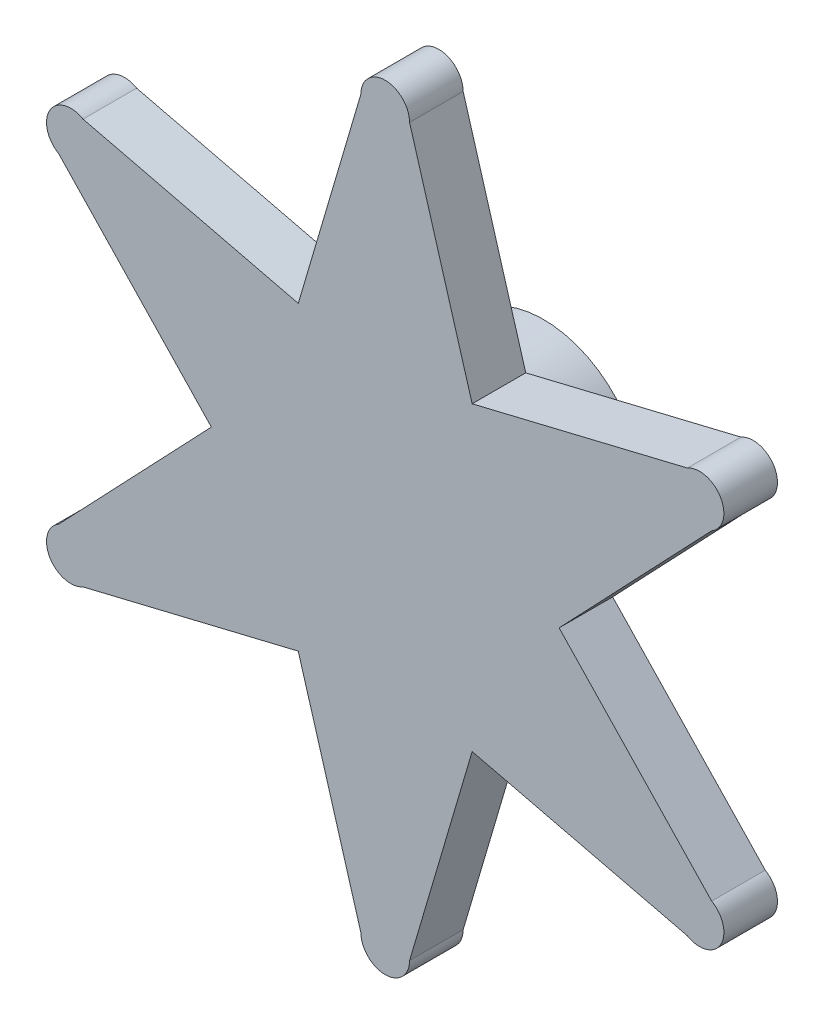
SolidWorks part; units mm, degrees
ref_plane "Front Plane" through (0, 0, 0) normal (0, 0, 1) x (1, 0, 0)
ref_plane "Top Plane" through (0, 0, 0) normal (0, 1, 0) x (1, 0, 0)
ref_plane "Right Plane" through (0, 0, 0) normal (1, 0, 0) x (0, 0, -1)
sketch "Sketch1" plane through (0, 0, 0) normal (0, 0, 1) x (1, 0, 0)
  line L200 (11.1072, 2.7986) -> (11.0109, 2.9361)
  line L201 (11.0109, 2.9361) -> (10.9327, 2.7877)
  line L202 (10.9327, 2.7877) -> (10.828, 2.9188)
  line L203 (10.828, 2.9188) -> (10.7592, 2.7657)
  line L204 (10.7592, 2.7657) -> (10.6465, 2.89)
  line L205 (10.6465, 2.89) -> (10.5874, 2.733)
  line L206 (10.5874, 2.733) -> (10.4672, 2.8499)
  line L207 (10.4672, 2.8499) -> (10.4181, 2.6895)
  line L208 (10.4181, 2.6895) -> (10.2907, 2.7987)
  line L209 (10.2907, 2.7987) -> (10.2518, 2.6355)
  line L210 (10.2518, 2.6355) -> (10.1178, 2.7364)
  line L211 (10.1178, 2.7364) -> (10.0893, 2.5711)
  line L212 (10.0893, 2.5711) -> (9.9492, 2.6635)
  line L213 (9.9492, 2.6635) -> (9.9311, 2.4967)
  line L214 (9.9311, 2.4967) -> (9.7855, 2.58)
  line L215 (9.7855, 2.58) -> (9.7778, 2.4124)
  line L216 (9.7778, 2.4124) -> (9.6273, 2.4865)
  line L217 (9.6273, 2.4865) -> (9.6302, 2.3187)
  line L218 (9.6302, 2.3187) -> (9.4753, 2.3832)
  line L219 (9.4753, 2.3832) -> (9.4888, 2.216)
  line L220 (9.4888, 2.216) -> (9.3301, 2.2706)
  line L221 (9.3301, 2.2706) -> (9.354, 2.1045)
  line L222 (9.354, 2.1045) -> (9.1923, 2.1491)
  line L223 (9.1923, 2.1491) -> (9.2266, 1.9848)
  line L224 (9.2266, 1.9848) -> (9.0624, 2.0191)
  line L225 (9.0624, 2.0191) -> (9.1069, 1.8574)
  line L226 (9.1069, 1.8574) -> (8.9408, 1.8813)
  line L227 (8.9408, 1.8813) -> (8.9955, 1.7227)
  line L228 (8.9955, 1.7227) -> (8.8282, 1.7361)
  line L229 (8.8282, 1.7361) -> (8.8927, 1.5812)
  line L230 (8.8927, 1.5812) -> (8.7249, 1.5841)
  line L231 (8.7249, 1.5841) -> (8.799, 1.4336)
  line L232 (8.799, 1.4336) -> (8.6314, 1.426)
  line L233 (8.6314, 1.426) -> (8.7148, 1.2804)
  line L234 (8.7148, 1.2804) -> (8.548, 1.2623)
  line L235 (8.548, 1.2623) -> (8.6403, 1.1222)
  line L236 (8.6403, 1.1222) -> (8.475, 1.0936)
  line L237 (8.475, 1.0936) -> (8.576, 0.9596)
  line L238 (8.576, 0.9596) -> (8.4128, 0.9207)
  line L239 (8.4128, 0.9207) -> (8.5219, 0.7933)
  line L240 (8.5219, 0.7933) -> (8.3615, 0.7443)
  line L241 (8.3615, 0.7443) -> (8.4785, 0.624)
  line L242 (8.4785, 0.624) -> (8.3214, 0.565)
  line L243 (8.3214, 0.565) -> (8.4457, 0.4522)
  line L244 (8.4457, 0.4522) -> (8.2927, 0.3835)
  line L245 (8.2927, 0.3835) -> (8.4238, 0.2788)
  line L246 (8.4238, 0.2788) -> (8.2754, 0.2005)
  line L247 (8.2754, 0.2005) -> (8.4128, 0.1043)
  line L248 (8.4128, 0.1043) -> (8.2696, 0.0169)
  line L249 (8.2696, 0.0169) -> (8.4128, -0.0706)
  line L250 (8.4128, -0.0706) -> (8.2754, -0.1668)
  line L251 (8.2754, -0.1668) -> (8.4238, -0.245)
  line L252 (8.4238, -0.245) -> (8.2927, -0.3497)
  line L253 (8.2927, -0.3497) -> (8.4457, -0.4185)
  line L254 (8.4457, -0.4185) -> (8.3214, -0.5312)
  line L255 (8.3214, -0.5312) -> (8.4785, -0.5903)
  line L256 (8.4785, -0.5903) -> (8.3615, -0.7105)
  line L257 (8.3615, -0.7105) -> (8.5219, -0.7596)
  line L258 (8.5219, -0.7596) -> (8.4128, -0.887)
  line L259 (8.4128, -0.887) -> (8.576, -0.9259)
  line L260 (8.576, -0.9259) -> (8.475, -1.0599)
  line L261 (8.475, -1.0599) -> (8.6403, -1.0884)
  line L262 (8.6403, -1.0884) -> (8.548, -1.2285)
  line L263 (8.548, -1.2285) -> (8.7148, -1.2466)
  line L264 (8.7148, -1.2466) -> (8.6314, -1.3922)
  line L265 (8.6314, -1.3922) -> (8.799, -1.3999)
  line L266 (8.799, -1.3999) -> (8.7249, -1.5504)
  line L267 (8.7249, -1.5504) -> (8.8927, -1.5475)
  line L268 (8.8927, -1.5475) -> (8.8282, -1.7024)
  line L269 (8.8282, -1.7024) -> (8.9955, -1.6889)
  line L270 (8.9955, -1.6889) -> (8.9408, -1.8476)
  line L271 (8.9408, -1.8476) -> (9.1069, -1.8237)
  line L272 (9.1069, -1.8237) -> (9.0624, -1.9854)
  line L273 (9.0624, -1.9854) -> (9.2266, -1.9511)
  line L274 (9.2266, -1.9511) -> (9.1923, -2.1153)
  line L275 (9.1923, -2.1153) -> (9.354, -2.0708)
  line L276 (9.354, -2.0708) -> (9.3301, -2.2369)
  line L277 (9.3301, -2.2369) -> (9.4888, -2.1822)
  line L278 (9.4888, -2.1822) -> (9.4753, -2.3495)
  line L279 (9.4753, -2.3495) -> (9.6302, -2.285)
  line L280 (9.6302, -2.285) -> (9.6273, -2.4528)
  line L281 (9.6273, -2.4528) -> (9.7778, -2.3787)
  line L282 (9.7778, -2.3787) -> (9.7855, -2.5463)
  line L283 (9.7855, -2.5463) -> (9.9311, -2.4629)
  line L284 (9.9311, -2.4629) -> (9.9492, -2.6297)
  line L285 (9.9492, -2.6297) -> (10.0893, -2.5374)
  line L286 (10.0893, -2.5374) -> (10.1178, -2.7027)
  line L287 (10.1178, -2.7027) -> (10.2518, -2.6017)
  line L288 (10.2518, -2.6017) -> (10.2907, -2.7649)
  line L289 (10.2907, -2.7649) -> (10.4181, -2.6558)
  line L290 (10.4181, -2.6558) -> (10.4672, -2.8162)
  line L291 (10.4672, -2.8162) -> (10.5874, -2.6992)
  line L292 (10.5874, -2.6992) -> (10.6465, -2.8563)
  line L293 (10.6465, -2.8563) -> (10.7592, -2.732)
  line L294 (10.7592, -2.732) -> (10.828, -2.885)
  line L295 (10.828, -2.885) -> (10.9327, -2.7539)
  line L296 (10.9327, -2.7539) -> (11.0109, -2.9023)
  line L297 (11.0109, -2.9023) -> (11.1072, -2.7649)
  line L298 (11.1072, -2.7649) -> (11.1946, -2.9081)
  line L299 (11.1946, -2.9081) -> (11.282, -2.7649)
  line L300 (11.282, -2.7649) -> (11.3782, -2.9023)
  line L301 (11.3782, -2.9023) -> (11.4565, -2.7539)
  line L302 (11.4565, -2.7539) -> (11.5612, -2.885)
  line L303 (11.5612, -2.885) -> (11.6299, -2.732)
  line L304 (11.6299, -2.732) -> (11.7427, -2.8563)
  line L305 (11.7427, -2.8563) -> (11.8017, -2.6992)
  line L306 (11.8017, -2.6992) -> (11.922, -2.8162)
  line L307 (11.922, -2.8162) -> (11.971, -2.6558)
  line L308 (11.971, -2.6558) -> (12.0984, -2.7649)
  line L309 (12.0984, -2.7649) -> (12.1373, -2.6017)
  line L310 (12.1373, -2.6017) -> (12.2713, -2.7027)
  line L311 (12.2713, -2.7027) -> (12.2999, -2.5374)
  line L312 (12.2999, -2.5374) -> (12.44, -2.6297)
  line L313 (12.44, -2.6297) -> (12.4581, -2.4629)
  line L314 (12.4581, -2.4629) -> (12.6037, -2.5463)
  line L315 (12.6037, -2.5463) -> (12.6113, -2.3787)
  line L316 (12.6113, -2.3787) -> (12.7618, -2.4528)
  line L317 (12.7618, -2.4528) -> (12.7589, -2.285)
  line L318 (12.7589, -2.285) -> (12.9138, -2.3495)
  line L319 (12.9138, -2.3495) -> (12.9004, -2.1822)
  line L320 (12.9004, -2.1822) -> (13.059, -2.2369)
  line L321 (13.059, -2.2369) -> (13.0351, -2.0708)
  line L322 (13.0351, -2.0708) -> (13.1968, -2.1153)
  line L323 (13.1968, -2.1153) -> (13.1625, -1.9511)
  line L324 (13.1625, -1.9511) -> (13.3268, -1.9854)
  line L325 (13.3268, -1.9854) -> (13.2822, -1.8237)
  line L326 (13.2822, -1.8237) -> (13.4483, -1.8476)
  line L327 (13.4483, -1.8476) -> (13.3937, -1.6889)
  line L328 (13.3937, -1.6889) -> (13.5609, -1.7024)
  line L329 (13.5609, -1.7024) -> (13.4965, -1.5475)
  line L330 (13.4965, -1.5475) -> (13.6642, -1.5504)
  line L331 (13.6642, -1.5504) -> (13.5901, -1.3999)
  line L332 (13.5901, -1.3999) -> (13.7577, -1.3922)
  line L333 (13.7577, -1.3922) -> (13.6744, -1.2466)
  line L334 (13.6744, -1.2466) -> (13.8412, -1.2285)
  line L335 (13.8412, -1.2285) -> (13.7488, -1.0884)
  line L336 (13.7488, -1.0884) -> (13.9141, -1.0599)
  line L337 (13.9141, -1.0599) -> (13.8132, -0.9259)
  line L338 (13.8132, -0.9259) -> (13.9764, -0.887)
  line L339 (13.9764, -0.887) -> (13.8672, -0.7596)
  line L340 (13.8672, -0.7596) -> (14.0276, -0.7105)
  line L341 (14.0276, -0.7105) -> (13.9107, -0.5903)
  line L342 (13.9107, -0.5903) -> (14.0677, -0.5312)
  line L343 (14.0677, -0.5312) -> (13.9434, -0.4185)
  line L344 (13.9434, -0.4185) -> (14.0965, -0.3497)
  line L345 (14.0965, -0.3497) -> (13.9654, -0.245)
  line L346 (13.9654, -0.245) -> (14.1138, -0.1668)
  line L347 (14.1138, -0.1668) -> (13.9763, -0.0706)
  line L348 (13.9763, -0.0706) -> (14.1195, 0.0169)
  line L349 (14.1195, 0.0169) -> (13.9763, 0.1043)
  line L350 (13.9763, 0.1043) -> (14.1138, 0.2005)
  line L351 (14.1138, 0.2005) -> (13.9654, 0.2788)
  line L352 (13.9654, 0.2788) -> (14.0965, 0.3835)
  line L353 (14.0965, 0.3835) -> (13.9434, 0.4522)
  line L354 (13.9434, 0.4522) -> (14.0677, 0.565)
  line L355 (14.0677, 0.565) -> (13.9107, 0.624)
  line L356 (13.9107, 0.624) -> (14.0276, 0.7443)
  line L357 (14.0276, 0.7443) -> (13.8672, 0.7933)
  line L358 (13.8672, 0.7933) -> (13.9764, 0.9207)
  line L359 (13.9764, 0.9207) -> (13.8132, 0.9596)
  line L360 (13.8132, 0.9596) -> (13.9141, 1.0936)
  line L361 (13.9141, 1.0936) -> (13.7488, 1.1222)
  line L362 (13.7488, 1.1222) -> (13.8412, 1.2623)
  line L363 (13.8412, 1.2623) -> (13.6744, 1.2804)
  line L364 (13.6744, 1.2804) -> (13.7577, 1.426)
  line L365 (13.7577, 1.426) -> (13.5901, 1.4336)
  line L366 (13.5901, 1.4336) -> (13.6642, 1.5841)
  line L367 (13.6642, 1.5841) -> (13.4965, 1.5812)
  line L368 (13.4965, 1.5812) -> (13.5609, 1.7361)
  line L369 (13.5609, 1.7361) -> (13.3937, 1.7227)
  line L370 (13.3937, 1.7227) -> (13.4483, 1.8813)
  line L371 (13.4483, 1.8813) -> (13.2822, 1.8574)
  line L372 (13.2822, 1.8574) -> (13.3268, 2.0191)
  line L373 (13.3268, 2.0191) -> (13.1625, 1.9848)
  line L374 (13.1625, 1.9848) -> (13.1968, 2.1491)
  line L375 (13.1968, 2.1491) -> (13.0351, 2.1045)
  line L376 (13.0351, 2.1045) -> (13.059, 2.2706)
  line L377 (13.059, 2.2706) -> (12.9004, 2.216)
  line L378 (12.9004, 2.216) -> (12.9138, 2.3832)
  line L379 (12.9138, 2.3832) -> (12.7589, 2.3187)
  line L380 (12.7589, 2.3187) -> (12.7618, 2.4865)
  line L381 (12.7618, 2.4865) -> (12.6113, 2.4124)
  line L382 (12.6113, 2.4124) -> (12.6037, 2.58)
  line L383 (12.6037, 2.58) -> (12.4581, 2.4967)
  line L384 (12.4581, 2.4967) -> (12.44, 2.6635)
  line L385 (12.44, 2.6635) -> (12.2999, 2.5711)
  line L386 (12.2999, 2.5711) -> (12.2713, 2.7364)
  line L387 (12.2713, 2.7364) -> (12.1373, 2.6355)
  line L388 (12.1373, 2.6355) -> (12.0984, 2.7987)
  line L389 (12.0984, 2.7987) -> (11.971, 2.6895)
  line L390 (11.971, 2.6895) -> (11.922, 2.8499)
  line L391 (11.922, 2.8499) -> (11.8017, 2.733)
  line L392 (11.8017, 2.733) -> (11.7427, 2.89)
  line L393 (11.7427, 2.89) -> (11.6299, 2.7657)
  line L394 (11.6299, 2.7657) -> (11.5612, 2.9188)
  line L395 (11.5612, 2.9188) -> (11.4565, 2.7877)
  line L396 (11.4565, 2.7877) -> (11.3782, 2.9361)
  line L397 (11.3782, 2.9361) -> (11.282, 2.7986)
  line L398 (11.282, 2.7986) -> (11.1946, 2.9418)
  line L399 (11.1946, 2.9418) -> (11.1072, 2.7986)
  line L400 (11.1072, 2.7986) -> (11.0109, 2.9361)
  line L401 (11.0109, 2.9361) -> (10.9327, 2.7877)
  line L402 (10.9327, 2.7877) -> (10.828, 2.9188)
  line L403 (10.828, 2.9188) -> (10.7592, 2.7657)
  line L404 (10.7592, 2.7657) -> (10.6465, 2.89)
  line L405 (10.6465, 2.89) -> (10.5874, 2.733)
  line L406 (10.5874, 2.733) -> (10.4672, 2.8499)
  line L407 (10.4672, 2.8499) -> (10.4181, 2.6895)
  line L408 (10.4181, 2.6895) -> (10.2907, 2.7987)
  line L409 (10.2907, 2.7987) -> (10.2518, 2.6355)
  line L410 (10.2518, 2.6355) -> (10.1178, 2.7364)
  line L411 (10.1178, 2.7364) -> (10.0893, 2.5711)
  line L412 (10.0893, 2.5711) -> (9.9492, 2.6635)
  line L413 (9.9492, 2.6635) -> (9.9311, 2.4967)
  line L414 (9.9311, 2.4967) -> (9.7855, 2.58)
  line L415 (9.7855, 2.58) -> (9.7778, 2.4124)
  line L416 (9.7778, 2.4124) -> (9.6273, 2.4865)
  line L417 (9.6273, 2.4865) -> (9.6302, 2.3187)
  line L418 (9.6302, 2.3187) -> (9.4753, 2.3832)
  line L419 (9.4753, 2.3832) -> (9.4888, 2.216)
  line L420 (9.4888, 2.216) -> (9.3301, 2.2706)
  line L421 (9.3301, 2.2706) -> (9.354, 2.1045)
  line L422 (9.354, 2.1045) -> (9.1923, 2.1491)
  line L423 (9.1923, 2.1491) -> (9.2266, 1.9848)
  line L424 (9.2266, 1.9848) -> (9.0624, 2.0191)
  line L425 (9.0624, 2.0191) -> (9.1069, 1.8574)
  line L426 (9.1069, 1.8574) -> (8.9408, 1.8813)
  line L427 (8.9408, 1.8813) -> (8.9955, 1.7227)
  line L428 (8.9955, 1.7227) -> (8.8282, 1.7361)
  line L429 (8.8282, 1.7361) -> (8.8927, 1.5812)
  line L430 (8.8927, 1.5812) -> (8.7249, 1.5841)
  line L431 (8.7249, 1.5841) -> (8.799, 1.4336)
  line L432 (8.799, 1.4336) -> (8.6314, 1.426)
  line L433 (8.6314, 1.426) -> (8.7148, 1.2804)
  line L434 (8.7148, 1.2804) -> (8.548, 1.2623)
  line L435 (8.548, 1.2623) -> (8.6403, 1.1222)
  line L436 (8.6403, 1.1222) -> (8.475, 1.0936)
  line L437 (8.475, 1.0936) -> (8.576, 0.9596)
  line L438 (8.576, 0.9596) -> (8.4128, 0.9207)
  line L439 (8.4128, 0.9207) -> (8.5219, 0.7933)
  line L440 (8.5219, 0.7933) -> (8.3615, 0.7443)
  line L441 (8.3615, 0.7443) -> (8.4785, 0.624)
  line L442 (8.4785, 0.624) -> (8.3214, 0.565)
  line L443 (8.3214, 0.565) -> (8.4457, 0.4522)
  line L444 (8.4457, 0.4522) -> (8.2927, 0.3835)
  line L445 (8.2927, 0.3835) -> (8.4238, 0.2788)
  line L446 (8.4238, 0.2788) -> (8.2754, 0.2005)
  line L447 (8.2754, 0.2005) -> (8.4128, 0.1043)
  line L448 (8.4128, 0.1043) -> (8.2696, 0.0169)
  line L449 (8.2696, 0.0169) -> (8.4128, -0.0706)
  line L450 (8.4128, -0.0706) -> (8.2754, -0.1668)
  line L451 (8.2754, -0.1668) -> (8.4238, -0.245)
  line L452 (8.4238, -0.245) -> (8.2927, -0.3497)
  line L453 (8.2927, -0.3497) -> (8.4457, -0.4185)
  line L454 (8.4457, -0.4185) -> (8.3214, -0.5312)
  line L455 (8.3214, -0.5312) -> (8.4785, -0.5903)
  line L456 (8.4785, -0.5903) -> (8.3615, -0.7105)
  line L457 (8.3615, -0.7105) -> (8.5219, -0.7596)
  line L458 (8.5219, -0.7596) -> (8.4128, -0.887)
  line L459 (8.4128, -0.887) -> (8.576, -0.9259)
  line L460 (8.576, -0.9259) -> (8.475, -1.0599)
  line L461 (8.475, -1.0599) -> (8.6403, -1.0884)
  line L462 (8.6403, -1.0884) -> (8.548, -1.2285)
  line L463 (8.548, -1.2285) -> (8.7148, -1.2466)
  line L464 (8.7148, -1.2466) -> (8.6314, -1.3922)
  line L465 (8.6314, -1.3922) -> (8.799, -1.3999)
  line L466 (8.799, -1.3999) -> (8.7249, -1.5504)
  line L467 (8.7249, -1.5504) -> (8.8927, -1.5475)
  line L468 (8.8927, -1.5475) -> (8.8282, -1.7024)
  line L469 (8.8282, -1.7024) -> (8.9955, -1.6889)
  line L470 (8.9955, -1.6889) -> (8.9408, -1.8476)
  line L471 (8.9408, -1.8476) -> (9.1069, -1.8237)
  line L472 (9.1069, -1.8237) -> (9.0624, -1.9854)
  line L473 (9.0624, -1.9854) -> (9.2266, -1.9511)
  line L474 (9.2266, -1.9511) -> (9.1923, -2.1153)
  line L475 (9.1923, -2.1153) -> (9.354, -2.0708)
  line L476 (9.354, -2.0708) -> (9.3301, -2.2369)
  line L477 (9.3301, -2.2369) -> (9.4888, -2.1822)
  line L478 (9.4888, -2.1822) -> (9.4753, -2.3495)
  line L479 (9.4753, -2.3495) -> (9.6302, -2.285)
  line L480 (9.6302, -2.285) -> (9.6273, -2.4528)
  line L481 (9.6273, -2.4528) -> (9.7778, -2.3787)
  line L482 (9.7778, -2.3787) -> (9.7855, -2.5463)
  line L483 (9.7855, -2.5463) -> (9.9311, -2.4629)
  line L484 (9.9311, -2.4629) -> (9.9492, -2.6297)
  line L485 (9.9492, -2.6297) -> (10.0893, -2.5374)
  line L486 (10.0893, -2.5374) -> (10.1178, -2.7027)
  line L487 (10.1178, -2.7027) -> (10.2518, -2.6017)
  line L488 (10.2518, -2.6017) -> (10.2907, -2.7649)
  line L489 (10.2907, -2.7649) -> (10.4181, -2.6558)
  line L490 (10.4181, -2.6558) -> (10.4672, -2.8162)
  line L491 (10.4672, -2.8162) -> (10.5874, -2.6992)
  line L492 (10.5874, -2.6992) -> (10.6465, -2.8563)
  line L493 (10.6465, -2.8563) -> (10.7592, -2.732)
  line L494 (10.7592, -2.732) -> (10.828, -2.885)
  line L495 (10.828, -2.885) -> (10.9327, -2.7539)
  line L496 (10.9327, -2.7539) -> (11.0109, -2.9023)
  line L497 (11.0109, -2.9023) -> (11.1072, -2.7649)
  line L498 (11.1072, -2.7649) -> (11.1946, -2.9081)
  line L499 (11.1946, -2.9081) -> (11.282, -2.7649)
  line L500 (11.282, -2.7649) -> (11.3782, -2.9023)
  line L501 (11.3782, -2.9023) -> (11.4565, -2.7539)
  line L502 (11.4565, -2.7539) -> (11.5612, -2.885)
  line L503 (11.5612, -2.885) -> (11.6299, -2.732)
  line L504 (11.6299, -2.732) -> (11.7427, -2.8563)
  line L505 (11.7427, -2.8563) -> (11.8017, -2.6992)
  line L506 (11.8017, -2.6992) -> (11.922, -2.8162)
  line L507 (11.922, -2.8162) -> (11.971, -2.6558)
  line L508 (11.971, -2.6558) -> (12.0984, -2.7649)
  line L509 (12.0984, -2.7649) -> (12.1373, -2.6017)
  line L510 (12.1373, -2.6017) -> (12.2713, -2.7027)
  line L511 (12.2713, -2.7027) -> (12.2999, -2.5374)
  line L512 (12.2999, -2.5374) -> (12.44, -2.6297)
  line L513 (12.44, -2.6297) -> (12.4581, -2.4629)
  line L514 (12.4581, -2.4629) -> (12.6037, -2.5463)
  line L515 (12.6037, -2.5463) -> (12.6113, -2.3787)
  line L516 (12.6113, -2.3787) -> (12.7618, -2.4528)
  line L517 (12.7618, -2.4528) -> (12.7589, -2.285)
  line L518 (12.7589, -2.285) -> (12.9138, -2.3495)
  line L519 (12.9138, -2.3495) -> (12.9004, -2.1822)
  line L520 (12.9004, -2.1822) -> (13.059, -2.2369)
  line L521 (13.059, -2.2369) -> (13.0351, -2.0708)
  line L522 (13.0351, -2.0708) -> (13.1968, -2.1153)
  line L523 (13.1968, -2.1153) -> (13.1625, -1.9511)
  line L524 (13.1625, -1.9511) -> (13.3268, -1.9854)
  line L525 (13.3268, -1.9854) -> (13.2822, -1.8237)
  line L526 (13.2822, -1.8237) -> (13.4483, -1.8476)
  line L527 (13.4483, -1.8476) -> (13.3937, -1.6889)
  line L528 (13.3937, -1.6889) -> (13.5609, -1.7024)
  line L529 (13.5609, -1.7024) -> (13.4965, -1.5475)
  line L530 (13.4965, -1.5475) -> (13.6642, -1.5504)
  line L531 (13.6642, -1.5504) -> (13.5901, -1.3999)
  line L532 (13.5901, -1.3999) -> (13.7577, -1.3922)
  line L533 (13.7577, -1.3922) -> (13.6744, -1.2466)
  line L534 (13.6744, -1.2466) -> (13.8412, -1.2285)
  line L535 (13.8412, -1.2285) -> (13.7488, -1.0884)
  line L536 (13.7488, -1.0884) -> (13.9141, -1.0599)
  line L537 (13.9141, -1.0599) -> (13.8132, -0.9259)
  line L538 (13.8132, -0.9259) -> (13.9764, -0.887)
  line L539 (13.9764, -0.887) -> (13.8672, -0.7596)
  line L540 (13.8672, -0.7596) -> (14.0276, -0.7105)
  line L541 (14.0276, -0.7105) -> (13.9107, -0.5903)
  line L542 (13.9107, -0.5903) -> (14.0677, -0.5312)
  line L543 (14.0677, -0.5312) -> (13.9434, -0.4185)
  line L544 (13.9434, -0.4185) -> (14.0965, -0.3497)
  line L545 (14.0965, -0.3497) -> (13.9654, -0.245)
  line L546 (13.9654, -0.245) -> (14.1138, -0.1668)
  line L547 (14.1138, -0.1668) -> (13.9763, -0.0706)
  line L548 (13.9763, -0.0706) -> (14.1195, 0.0169)
  line L549 (14.1195, 0.0169) -> (13.9763, 0.1043)
  line L550 (13.9763, 0.1043) -> (14.1138, 0.2005)
  line L551 (14.1138, 0.2005) -> (13.9654, 0.2788)
  line L552 (13.9654, 0.2788) -> (14.0965, 0.3835)
  line L553 (14.0965, 0.3835) -> (13.9434, 0.4522)
  line L554 (13.9434, 0.4522) -> (14.0677, 0.565)
  line L555 (14.0677, 0.565) -> (13.9107, 0.624)
  line L556 (13.9107, 0.624) -> (14.0276, 0.7443)
  line L557 (14.0276, 0.7443) -> (13.8672, 0.7933)
  line L558 (13.8672, 0.7933) -> (13.9764, 0.9207)
  line L559 (13.9764, 0.9207) -> (13.8132, 0.9596)
  line L560 (13.8132, 0.9596) -> (13.9141, 1.0936)
  line L561 (13.9141, 1.0936) -> (13.7488, 1.1222)
  line L562 (13.7488, 1.1222) -> (13.8412, 1.2623)
  line L563 (13.8412, 1.2623) -> (13.6744, 1.2804)
  line L564 (13.6744, 1.2804) -> (13.7577, 1.426)
  line L565 (13.7577, 1.426) -> (13.5901, 1.4336)
  line L566 (13.5901, 1.4336) -> (13.6642, 1.5841)
  line L567 (13.6642, 1.5841) -> (13.4965, 1.5812)
  line L568 (13.4965, 1.5812) -> (13.5609, 1.7361)
  line L569 (13.5609, 1.7361) -> (13.3937, 1.7227)
  line L570 (13.3937, 1.7227) -> (13.4483, 1.8813)
  line L571 (13.4483, 1.8813) -> (13.2822, 1.8574)
  line L572 (13.2822, 1.8574) -> (13.3268, 2.0191)
  line L573 (13.3268, 2.0191) -> (13.1625, 1.9848)
  line L574 (13.1625, 1.9848) -> (13.1968, 2.1491)
  line L575 (13.1968, 2.1491) -> (13.0351, 2.1045)
  line L576 (13.0351, 2.1045) -> (13.059, 2.2706)
  line L577 (13.059, 2.2706) -> (12.9004, 2.216)
  line L578 (12.9004, 2.216) -> (12.9138, 2.3832)
  line L579 (12.9138, 2.3832) -> (12.7589, 2.3187)
  line L580 (12.7589, 2.3187) -> (12.7618, 2.4865)
  line L581 (12.7618, 2.4865) -> (12.6113, 2.4124)
  line L582 (12.6113, 2.4124) -> (12.6037, 2.58)
  line L583 (12.6037, 2.58) -> (12.4581, 2.4967)
  line L584 (12.4581, 2.4967) -> (12.44, 2.6635)
  line L585 (12.44, 2.6635) -> (12.2999, 2.5711)
  line L586 (12.2999, 2.5711) -> (12.2713, 2.7364)
  line L587 (12.2713, 2.7364) -> (12.1373, 2.6355)
  line L588 (12.1373, 2.6355) -> (12.0984, 2.7987)
  line L589 (12.0984, 2.7987) -> (11.971, 2.6895)
  line L590 (11.971, 2.6895) -> (11.922, 2.8499)
  line L591 (11.922, 2.8499) -> (11.8017, 2.733)
  line L592 (11.8017, 2.733) -> (11.7427, 2.89)
  line L593 (11.7427, 2.89) -> (11.6299, 2.7657)
  line L594 (11.6299, 2.7657) -> (11.5612, 2.9188)
  line L595 (11.5612, 2.9188) -> (11.4565, 2.7877)
  line L596 (11.4565, 2.7877) -> (11.3782, 2.9361)
  line L597 (11.3782, 2.9361) -> (11.282, 2.7986)
  line L598 (11.282, 2.7986) -> (11.1946, 2.9418)
  line L599 (11.1946, 2.9418) -> (11.1072, 2.7986)
  circle A0 centre (11.1946, 0) radius 4.0454
  dimension "D1" = 0
extrude "Boss-Extrude1" add sketch "Sketch1" against normal blind 3.8 and the other way blind 0.5
sketch "Sketch3" plane through (0, 0, 0.5) normal (0, 0, 1) x (1, 0, 0)
  line L0 (11.1946, 0) -> (11.1946, 5.0261) construction
  line L1 (7.6244, 6.0792) -> (10.1946, 14.8)
  line L2 (12.1946, 14.8) -> (14.7648, 6.0792)
  line L3 (14.7648, 6.0792) -> (23.6023, 8.2137)
  line L4 (24.6023, 6.4817) -> (18.335, -0.1046)
  line L5 (18.335, -0.1046) -> (24.6023, -6.6909)
  line L6 (23.6023, -8.4229) -> (14.7648, -6.2883)
  line L7 (14.7648, -6.2883) -> (12.1946, -15.0092)
  line L8 (10.1946, -15.0092) -> (7.6244, -6.2883)
  line L9 (7.6244, -6.2883) -> (-1.2132, -8.4229)
  line L10 (-2.2132, -6.6909) -> (4.0542, -0.1046)
  line L11 (4.0542, -0.1046) -> (-2.2132, 6.4817)
  line L12 (-1.2132, 8.2137) -> (7.6244, 6.0792)
  arc A1 (12.1946, 14.8) -> (10.1946, 14.8) centre (11.1946, 14.8) ccw
  arc A2 (24.6023, 6.4817) -> (23.6023, 8.2137) centre (24.1023, 7.3477) ccw
  arc A3 (23.6023, -8.4229) -> (24.6023, -6.6909) centre (24.1023, -7.5569) ccw
  arc A4 (10.1946, -15.0092) -> (12.1946, -15.0092) centre (11.1946, -15.0092) ccw
  arc A5 (-2.2132, -6.6909) -> (-1.2132, -8.4229) centre (-1.7132, -7.5569) ccw
  arc A6 (-1.2132, 8.2137) -> (-2.2132, 6.4817) centre (-1.7132, 7.3477) ccw
  point P38 (11.1946, -0.1046)
  dimension "D2" = 2
extrude "Boss-Extrude2" add sketch "Sketch3" along normal blind 2.2
